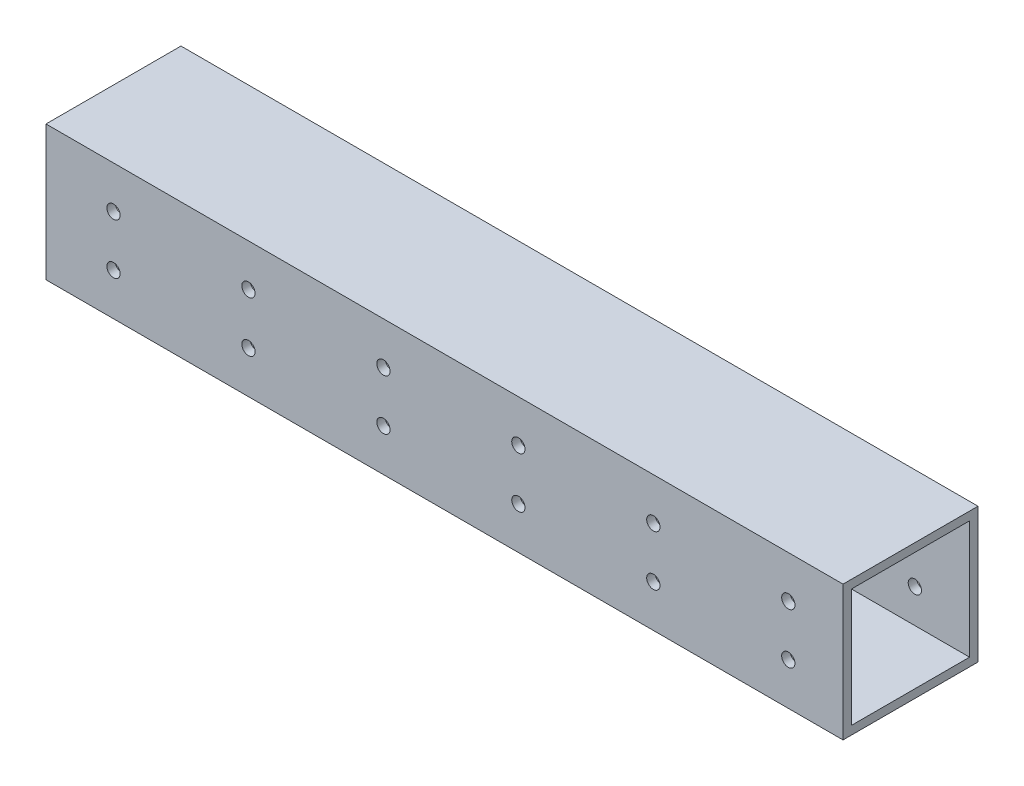
SolidWorks part; units mm, degrees
ref_plane "Front Plane" through (0, 0, 0) normal (0, 0, 1) x (1, 0, 0)
ref_plane "Top Plane" through (0, 0, 0) normal (0, 1, 0) x (1, 0, 0)
ref_plane "Right Plane" through (0, 0, 0) normal (1, 0, 0) x (0, 0, -1)
sketch "Sketch1" plane through (0, 0, 0) normal (1, 0, 0) x (0, 0, -1)
  line L0 (3.175, 47.625) -> (47.625, 47.625)
  line L1 (0, 0) -> (50.8, 0)
  line L2 (0, 0) -> (0, 50.8)
  line L3 (0, 50.8) -> (50.8, 50.8)
  line L4 (50.8, 0) -> (50.8, 50.8)
  line L5 (47.625, 3.175) -> (47.625, 47.625)
  line L6 (3.175, 3.175) -> (47.625, 3.175)
  line L7 (3.175, 3.175) -> (3.175, 47.625)
  dimension "D1" = 50.8
  dimension "D2" = 50.8
  dimension "D3" = 3.175
extrude "Boss-Extrude1" add sketch "Sketch1" along normal blind 300 contours L1 L4 L3 L2 L6 L7 L0 L5
sketch "Sketch2" plane through (0, 0, 0) normal (0, 0, 1) x (1, 0, 0)
  line L0 (300, 0) -> (0, 0) construction
  line L2 (0, 0) -> (0, 50.8) construction
  circle A0 centre (25.4, 15.875) radius 2.5
  circle A1 centre (76.2, 15.875) radius 2.5
  circle A2 centre (127, 15.875) radius 2.5
  circle A3 centre (177.8, 15.875) radius 2.5
  circle A4 centre (228.6, 15.875) radius 2.5
  circle A5 centre (279.4, 15.875) radius 2.5
  circle A6 centre (76.2, 34.925) radius 2.5
  circle A7 centre (127, 34.925) radius 2.5
  circle A8 centre (177.8, 34.925) radius 2.5
  circle A9 centre (228.6, 34.925) radius 2.5
  circle A10 centre (279.4, 34.925) radius 2.5
  circle A11 centre (25.4, 34.925) radius 2.5
  dimension "D1" = 5
  dimension "D2" = 15.875
  dimension "D5" = 25.4
  dimension "D6" = 25.4
  dimension "D7" = 76.2
  dimension "D8" = 34.925
  dimension "D3" = 6
  dimension "D4" = 2
extrude "Cut-Extrude1" cut sketch "Sketch2" against normal blind 300
